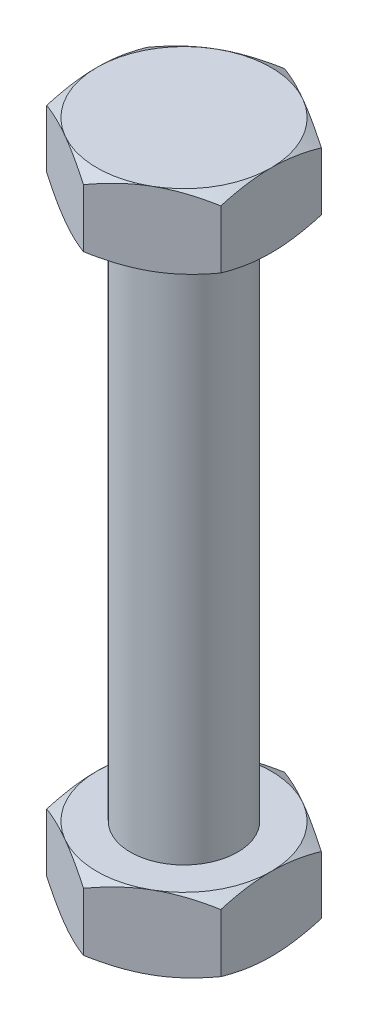
SolidWorks part; units mm, degrees
ref_plane "前视基准面" through (0, 0, 0) normal (0, 0, 1) x (1, 0, 0)
ref_plane "上视基准面" through (0, 0, 0) normal (0, 1, 0) x (1, 0, 0)
ref_plane "右视基准面" through (0, 0, 0) normal (1, 0, 0) x (0, 0, -1)
other "Configuration Table"
sketch "草图1" plane through (0, 0, 0) normal (0, 0, 1) x (1, 0, 0)
  line L0 (0, 25.5) -> (10, 25.5)
  line L1 (10, 25.5) -> (10, 20)
  line L2 (10, 20) -> (4, 20)
  line L3 (4, 20) -> (4, -20)
  line L4 (4, -20) -> (10, -20)
  line L5 (10, -20) -> (10, -25.5)
  line L6 (10, -25.5) -> (0, -25.5)
  line L7 (0, -25.5) -> (0, 25.5)
  line L8 (0, 0) -> (0, 21.8548) construction
  dimension "D1" = 4
  dimension "D2" = 5.5
  dimension "D3" = 10
  dimension "D4" = 40
revolve "旋转1" add sketch "草图1" angle 360 about L8
sketch "草图2" plane through (0, 25.5, 0) normal (0, 1, 0) x (1, 0, 0)
  line L1 (0, 7.5056) -> (-6.5, 3.7528)
  line L2 (-6.5, 3.7528) -> (-6.5, -3.7528)
  line L3 (-6.5, -3.7528) -> (0, -7.5056)
  line L4 (0, -7.5056) -> (6.5, -3.7528)
  line L5 (6.5, -3.7528) -> (6.5, 3.7528)
  line L6 (6.5, 3.7528) -> (0, 7.5056)
  circle A0 centre (0, 0) radius 6.5 construction
  circle A1 centre (0, 0) radius 12.5
  dimension "D1" = 13
  dimension "D2" = 25
extrude "切除-拉伸1" cut sketch "草图2" against normal through all
sketch "草图3" plane through (0, 0, 0) normal (0, 0, 1) x (1, 0, 0)
  line L0 (0, 0) -> (0, 28.6168) construction
  line L1 (6.5, 25.5) -> (9, 25.5)
  line L2 (9, 25.5) -> (9, 24.0566)
  line L3 (9, 24.0566) -> (6.5, 25.5)
  line L4 (9, 21.4434) -> (9, 20)
  line L5 (9, 20) -> (6.5, 20)
  line L6 (6.5, 20) -> (9, 21.4434)
  line L7 (6.5, -20) -> (9, -20)
  line L8 (9, -20) -> (9, -21.4434)
  line L9 (9, -21.4434) -> (6.5, -20)
  line L10 (6.5, -25.5) -> (9, -25.5)
  line L11 (9, -25.5) -> (9, -24.0566)
  line L12 (9, -24.0566) -> (6.5, -25.5)
  line L13 (0, 25.5) -> (6.5, 25.5) construction
  line L14 (6.5, 20) -> (0, 20) construction
  line L15 (0, -20) -> (6.5, -20) construction
  line L16 (0, -25.5) -> (6.5, -25.5) construction
  dimension "D1" = 9
  dimension "D2" = 30
  dimension "D3" = 6.5
revolve "切除-旋转1" cut sketch "草图3" angle 360 about L0
